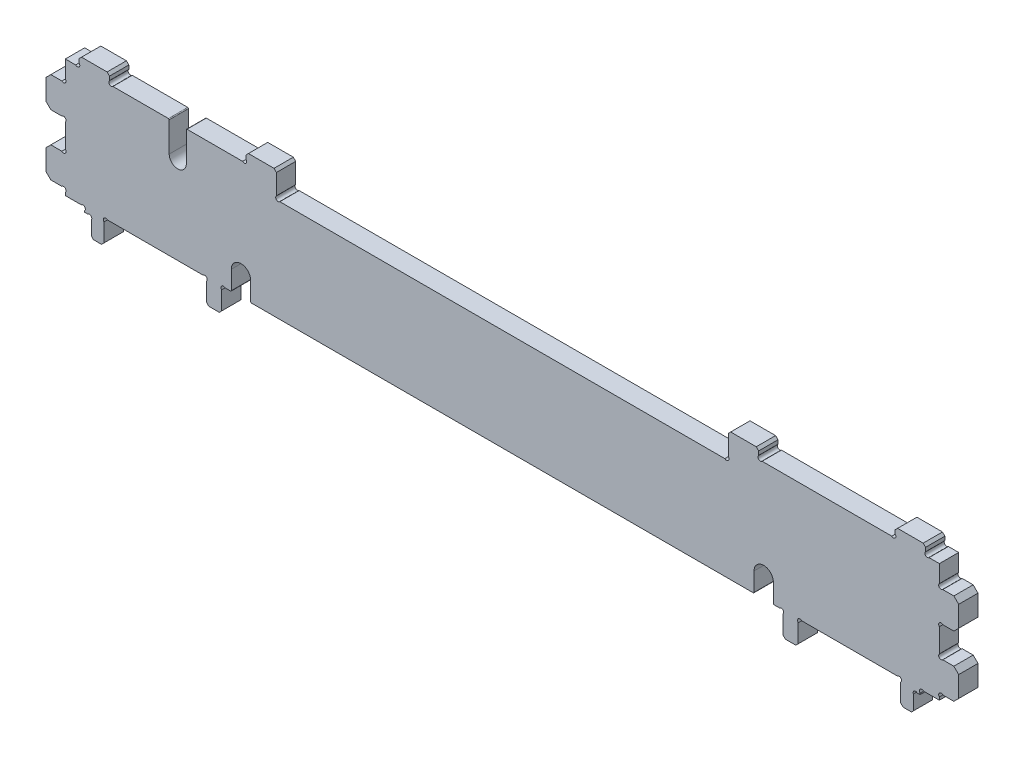
SolidWorks part; units mm, degrees
material "PVC Rigid"
ref_plane "Front Plane" through (0, 0, 0) normal (0, 0, 1) x (1, 0, 0)
ref_plane "Top Plane" through (0, 0, 0) normal (0, 1, 0) x (1, 0, 0)
ref_plane "Right Plane" through (0, 0, 0) normal (1, 0, 0) x (0, 0, -1)
sketch "Model" plane through (0, 0, 0) normal (0, 0, 1) x (1, 0, 0)
  line L0 (138.1552, -67.6125) -> (138.949, -66.8188)
  line L1 (134.6215, -66.8188) -> (135.4153, -67.6125)
  line L2 (100.1328, -67.6125) -> (100.9265, -66.8188)
  line L3 (95.9265, -66.8188) -> (96.7203, -67.6125)
  line L4 (-89.3772, -67.6125) -> (-88.5835, -66.8188)
  line L5 (-93.5835, -66.8188) -> (-92.7897, -67.6125)
  line L6 (-128.0722, -67.6125) -> (-127.2785, -66.8188)
  line L7 (-131.5077, -66.8188) -> (-130.7139, -67.6125)
  line L8 (-146.3285, -56.025) -> (-144.741, -57.6125)
  line L9 (-144.741, -47.6125) -> (-146.3285, -49.2)
  line L10 (-146.3285, -36.025) -> (-144.741, -37.6125)
  line L11 (-144.741, -27.6125) -> (-146.3285, -29.2)
  line L12 (-134.6597, -17.6125) -> (-135.4535, -18.4063)
  line L13 (-125.4535, -18.4063) -> (-126.2472, -17.6125)
  line L14 (-79.7957, -17.6125) -> (-80.5895, -18.4063)
  line L15 (-70.5895, -18.4063) -> (-71.3832, -17.6125)
  line L16 (-69.4669, -26.1597) -> (76.81, -26.1597)
  line L17 (78.7263, -17.6125) -> (77.9325, -18.4063)
  line L18 (87.9325, -18.4063) -> (87.1388, -17.6125)
  line L19 (133.5903, -17.6125) -> (132.7965, -18.4063)
  line L20 (142.7965, -18.4063) -> (142.0028, -17.6125)
  line L21 (153.6715, -29.2) -> (152.084, -27.6125)
  line L22 (152.084, -37.6125) -> (153.6715, -36.025)
  line L23 (153.6715, -49.2) -> (152.084, -47.6125)
  line L24 (152.084, -57.6125) -> (153.6715, -56.025)
  line L25 (102.0491, -59.6877) -> (133.499, -59.6877)
  line L26 (100.9265, -66.8188) -> (100.9265, -60.8103)
  line L27 (96.7203, -67.6125) -> (100.1328, -67.6125)
  line L28 (95.9265, -60.8103) -> (95.9265, -66.8188)
  line L29 (-87.4609, -59.6877) -> (94.804, -59.6877)
  line L30 (-88.5835, -66.8188) -> (-88.5835, -60.8103)
  line L31 (-92.7897, -67.6125) -> (-89.3772, -67.6125)
  line L32 (-93.5835, -60.8103) -> (-93.5835, -66.8188)
  line L33 (-126.1559, -59.6877) -> (-94.706, -59.6877)
  line L34 (-127.2785, -66.8188) -> (-127.2785, -60.8103)
  line L35 (-130.7139, -67.6125) -> (-128.0722, -67.6125)
  line L36 (-131.5077, -62.3851) -> (-131.5077, -66.8188)
  line L37 (-133.6285, -61.2625) -> (-132.6302, -61.2625)
  line L38 (-133.6285, -60.8103) -> (-133.6285, -61.2625)
  line L39 (-139.9785, -59.6877) -> (-134.751, -59.6877)
  line L40 (-139.9785, -58.7351) -> (-139.9785, -59.6877)
  line L41 (-144.741, -57.6125) -> (-141.101, -57.6125)
  line L42 (-146.3285, -49.2) -> (-146.3285, -56.025)
  line L43 (-141.101, -47.6125) -> (-144.741, -47.6125)
  line L44 (-139.9785, -38.7351) -> (-139.9785, -46.49)
  line L45 (-144.741, -37.6125) -> (-141.101, -37.6125)
  line L46 (-146.3285, -29.2) -> (-146.3285, -36.025)
  line L47 (-141.101, -27.6125) -> (-144.741, -27.6125)
  line L48 (-139.9785, -20.7875) -> (-139.9785, -26.49)
  line L49 (-136.576, -20.7875) -> (-139.9785, -20.7875)
  line L50 (-135.4535, -18.4063) -> (-135.4535, -19.665)
  line L51 (-126.2472, -17.6125) -> (-134.6597, -17.6125)
  line L52 (-125.4535, -19.665) -> (-125.4535, -18.4063)
  line L53 (-105.5215, -20.7875) -> (-124.3309, -20.7875)
  line L54 (-105.5215, -29.665) -> (-105.5215, -20.7875)
  line L55 (-101.644, -30.7875) -> (-104.3989, -30.7875)
  line L56 (-100.5215, -20.7875) -> (-100.5215, -29.665)
  line L57 (-81.712, -20.7875) -> (-100.5215, -20.7875)
  line L58 (-80.5895, -18.4063) -> (-80.5895, -19.665)
  line L59 (-71.3832, -17.6125) -> (-79.7957, -17.6125)
  line L60 (-70.5895, -25.0372) -> (-70.5895, -18.4063)
  line L61 (77.9325, -18.4063) -> (77.9325, -25.0372)
  line L62 (87.1388, -17.6125) -> (78.7263, -17.6125)
  line L63 (87.9325, -19.665) -> (87.9325, -18.4063)
  line L64 (131.674, -20.7875) -> (89.0551, -20.7875)
  line L65 (132.7965, -18.4063) -> (132.7965, -19.665)
  line L66 (142.0028, -17.6125) -> (133.5903, -17.6125)
  line L67 (142.7965, -19.665) -> (142.7965, -18.4063)
  line L68 (147.3215, -20.7875) -> (143.9191, -20.7875)
  line L69 (147.3215, -26.49) -> (147.3215, -20.7875)
  line L70 (152.084, -27.6125) -> (148.4441, -27.6125)
  line L71 (153.6715, -36.025) -> (153.6715, -29.2)
  line L72 (148.4441, -37.6125) -> (152.084, -37.6125)
  line L73 (147.3215, -46.49) -> (147.3215, -38.7351)
  line L74 (152.084, -47.6125) -> (148.4441, -47.6125)
  line L75 (153.6715, -56.025) -> (153.6715, -49.2)
  line L76 (148.4441, -57.6125) -> (152.084, -57.6125)
  line L77 (147.3215, -59.6877) -> (147.3215, -58.7351)
  line L78 (142.0941, -59.6877) -> (147.3215, -59.6877)
  line L79 (140.9715, -61.2625) -> (140.9715, -60.8103)
  line L80 (140.0715, -61.2625) -> (140.9715, -61.2625)
  line L81 (138.949, -66.8188) -> (138.949, -62.3851)
  line L82 (135.4153, -67.6125) -> (138.1552, -67.6125)
  line L83 (134.6215, -60.8103) -> (134.6215, -66.8188)
  arc A0 (-70.5895, -25.0372) -> (-69.4669, -26.1597) centre (-70.0282, -25.5985) ccw
  arc A1 (76.81, -26.1597) -> (77.9325, -25.0372) centre (77.3713, -25.5985) ccw
  arc A2 (102.0491, -59.6877) -> (100.9265, -60.8103) centre (101.4878, -60.249) ccw
  arc A3 (95.9265, -60.8103) -> (94.804, -59.6877) centre (95.3653, -60.249) ccw
  arc A4 (-87.4609, -59.6877) -> (-88.5835, -60.8103) centre (-88.0222, -60.249) ccw
  arc A5 (-93.5835, -60.8103) -> (-94.706, -59.6877) centre (-94.1447, -60.249) ccw
  arc A6 (-126.1559, -59.6877) -> (-127.2785, -60.8103) centre (-126.7172, -60.249) ccw
  arc A7 (-131.5077, -62.3851) -> (-132.6302, -61.2625) centre (-132.069, -61.8238) ccw
  arc A8 (-133.6285, -60.8103) -> (-134.751, -59.6877) centre (-134.1897, -60.249) ccw
  arc A9 (-139.9785, -58.7351) -> (-141.101, -57.6125) centre (-140.5397, -58.1738) ccw
  arc A10 (-141.101, -47.6125) -> (-139.9785, -46.49) centre (-140.5397, -47.0513) ccw
  arc A11 (-139.9785, -38.7351) -> (-141.101, -37.6125) centre (-140.5397, -38.1738) ccw
  arc A12 (-141.101, -27.6125) -> (-139.9785, -26.49) centre (-140.5397, -27.0513) ccw
  arc A13 (-136.576, -20.7875) -> (-135.4535, -19.665) centre (-136.0147, -20.2263) ccw
  arc A14 (-125.4535, -19.665) -> (-124.3309, -20.7875) centre (-124.8922, -20.2263) ccw
  arc A15 (-105.5215, -29.665) -> (-104.3989, -30.7875) centre (-104.9602, -30.2263) ccw
  arc A16 (-101.644, -30.7875) -> (-100.5215, -29.665) centre (-101.0827, -30.2263) ccw
  arc A17 (-81.712, -20.7875) -> (-80.5895, -19.665) centre (-81.1507, -20.2263) ccw
  arc A18 (87.9325, -19.665) -> (89.0551, -20.7875) centre (88.4938, -20.2263) ccw
  arc A19 (131.674, -20.7875) -> (132.7965, -19.665) centre (132.2353, -20.2263) ccw
  arc A20 (142.7965, -19.665) -> (143.9191, -20.7875) centre (143.3578, -20.2263) ccw
  arc A21 (147.3215, -26.49) -> (148.4441, -27.6125) centre (147.8828, -27.0513) ccw
  arc A22 (148.4441, -37.6125) -> (147.3215, -38.7351) centre (147.8828, -38.1738) ccw
  arc A23 (147.3215, -46.49) -> (148.4441, -47.6125) centre (147.8828, -47.0513) ccw
  arc A24 (148.4441, -57.6125) -> (147.3215, -58.7351) centre (147.8828, -58.1738) ccw
  arc A25 (142.0941, -59.6877) -> (140.9715, -60.8103) centre (141.5328, -60.249) ccw
  arc A26 (140.0715, -61.2625) -> (138.949, -62.3851) centre (139.5102, -61.8238) ccw
  arc A27 (134.6215, -60.8103) -> (133.499, -59.6877) centre (134.0603, -60.249) ccw
extrude "Boss-Extrude1" add sketch "Model" along normal blind 6.35
sketch "Sketch3" plane through (0, 0, 6.35) normal (0, 0, 1) x (1, 0, 0)
  line L0 (-131.3553, -62.1713) -> (-131.3553, -66.9712)
  line L1 (-131.5077, -66.8188) -> (-130.7139, -67.6125) construction
  line L2 (-131.5077, -62.3851) -> (-131.5077, -66.8188) construction
  line L3 (-131.5077, -62.3851) -> (-131.5077, -66.8188)
  line L4 (-131.5077, -66.8188) -> (-131.3553, -66.9712)
  line L5 (138.7966, -62.1713) -> (138.7966, -66.9712)
  line L7 (138.1552, -67.6125) -> (138.949, -66.8188) construction
  line L8 (138.949, -66.8188) -> (138.949, -62.3851) construction
  line L9 (138.7966, -66.9712) -> (138.949, -66.8188)
  line L10 (138.949, -66.8188) -> (138.949, -62.3851)
  arc A0 (-131.5077, -62.3851) -> (-132.6302, -61.2625) centre (-132.069, -61.8238) ccw construction
  arc A1 (-131.5077, -62.3851) -> (-131.3553, -62.1713) centre (-132.069, -61.8238) ccw
  arc A4 (140.0715, -61.2625) -> (138.949, -62.3851) centre (139.5102, -61.8238) ccw construction
  arc A5 (138.7966, -62.1713) -> (138.949, -62.3851) centre (139.5102, -61.8238) ccw
  dimension "D1" = 0.1524
  dimension "D2" = 0.1524
extrude "Cut-Extrude2" cut sketch "Sketch3" against normal through all
sketch "Sketch4" plane through (0, 0, 6.35) normal (0, 0, 1) x (1, 0, 0)
  line L0 (-87.4609, -59.6877) -> (94.804, -59.6877) construction
  line L1 (-85.4085, -59.6877) -> (-79.0585, -59.6877)
  line L2 (-85.4085, -59.6877) -> (-85.4085, -53.3377)
  line L4 (-79.0585, -59.6877) -> (-79.0585, -53.3377)
  line L5 (-88.5835, -66.8188) -> (-88.5835, -60.8103) construction
  line L6 (-139.9785, -20.7875) -> (147.3215, -59.6877) construction
  line L7 (3.6715, -54.3155) -> (3.6715, -26.1597) construction
  line L8 (76.81, -26.1597) -> (-69.4669, -26.1597) construction
  line L9 (86.4015, -59.6877) -> (86.4015, -53.3377)
  line L10 (92.7515, -59.6877) -> (92.7515, -53.3377)
  line L11 (92.7515, -59.6877) -> (86.4015, -59.6877)
  arc A0 (-79.0585, -53.3377) -> (-85.4085, -53.3377) centre (-82.2335, -53.3377) ccw
  arc A1 (86.4015, -53.3377) -> (92.7515, -53.3377) centre (89.5765, -53.3377) cw
  point P19 (3.6715, -40.2376)
  dimension "D2" = 6.35
  dimension "D1" = 3.175
  dimension "D3" = 6.35
  dimension "D4" = 6.35
extrude "Cut-Extrude3" cut sketch "Sketch4" against normal through all
sketch "Sketch6" plane through (0, 0, 6.35) normal (0, 0, 1) x (1, 0, 0)
  line L0 (-101.644, -30.7875) -> (-104.3989, -30.7875) construction
  line L1 (-81.712, -20.7875) -> (-100.5215, -20.7875) construction
  line L3 (-105.8335, -30.7875) -> (-105.8335, -20.7875)
  line L4 (-105.8335, -20.7875) -> (-100.2094, -20.7875)
  line L5 (-100.2094, -30.7875) -> (-100.2094, -20.7875)
  arc A0 (-105.8335, -30.7875) -> (-100.2094, -30.7875) centre (-103.0215, -30.7875) ccw
  arc A1 (-101.644, -30.7875) -> (-100.5215, -29.665) centre (-101.0827, -30.2263) ccw construction
extrude "Cut-Extrude4" cut sketch "Sketch6" against normal through all
fillet "Fillet1" radius 0.254 6 edges at (86.4015, -59.6877, 3.175) (92.7515, -59.6877, 3.175) (-79.0585, -59.6877, 3.175) (-85.4085, -59.6877, 3.175) (-105.8335, -20.7875, 3.175) (-100.2094, -20.7875, 3.175)
sketch "Sketch7" plane through (0, 0, 6.35) normal (0, 0, 1) x (1, 0, 0)
  line L0 (-79.0585, -59.4337) -> (-79.0585, -53.3377) construction
  line L1 (-78.8045, -59.6877) -> (86.1475, -59.6877) construction
  circle A0 centre (-77.0265, -57.6557) radius 0.7937
  dimension "D1" = 1.5875
  dimension "D2" = 2.032
  dimension "D3" = 2.032
extrude "Cut-Extrude5" [suppressed] cut sketch "Sketch7" against normal blind 2.54
pattern_linear "LPattern1" [suppressed] count 4 spacing 2.54
